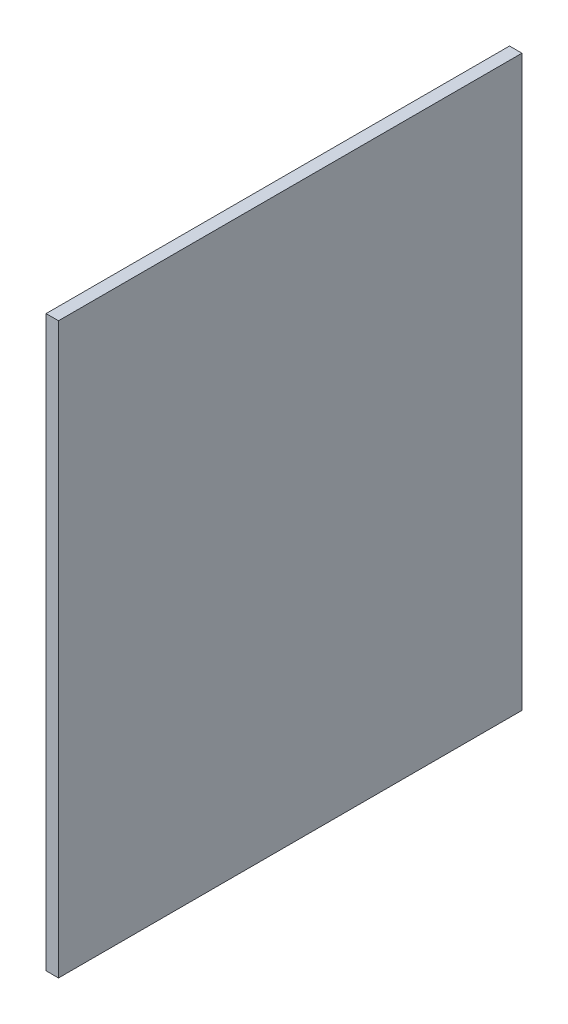
SolidWorks part; units mm, degrees
material "Acrylic (Medium-high impact)"
ref_plane "Front Plane" through (0, 0, 0) normal (0, 0, 1) x (1, 0, 0)
ref_plane "Top Plane" through (0, 0, 0) normal (0, 1, 0) x (1, 0, 0)
ref_plane "Right Plane" through (0, 0, 0) normal (1, 0, 0) x (0, 0, -1)
sketch "Sketch2" plane through (0, 0, 0) normal (1, 0, 0) x (0, 0, -1)
  line L1 (-409.575, 517.525) -> (409.575, 517.525)
  line L2 (-409.575, 517.525) -> (-409.575, -517.525)
  line L3 (-409.575, -517.525) -> (409.575, -517.525)
  line L4 (409.575, 517.525) -> (409.575, -517.525)
  line L5 (-409.575, 517.525) -> (409.575, -517.525) construction
  line L6 (-409.575, -517.525) -> (409.575, 517.525) construction
  point P0 (0, 0)
extrude "Boss-Extrude1" add sketch "Sketch2" along normal blind 25.4
sketch "Sketch3" plane through (25.4, 0, 0) normal (1, 0, 0) x (0, 0, -1)
  line L1 (447.675, -555.625) -> (-447.675, -555.625)
  line L2 (447.675, -555.625) -> (447.675, 555.625)
  line L3 (447.675, 555.625) -> (-447.675, 555.625)
  line L4 (409.575, -517.525) -> (409.575, 517.525)
  line L5 (409.575, 517.525) -> (-409.575, 517.525)
  line L6 (-409.575, 517.525) -> (-409.575, -517.525)
  line L7 (-409.575, -517.525) -> (409.575, -517.525)
  line L8 (409.575, -517.525) -> (409.575, 517.525)
  line L9 (409.575, 517.525) -> (-409.575, 517.525)
  line L10 (-409.575, 517.525) -> (-409.575, -517.525)
  line L11 (-409.575, -517.525) -> (409.575, -517.525)
  line L12 (-447.675, -555.625) -> (-447.675, 555.625)
  line L13 (447.675, -555.625) -> (-447.675, 555.625) construction
  line L14 (447.675, 555.625) -> (-447.675, -555.625) construction
  point P2 (0, 0)
  dimension "D1" = 0
extrude "Boss-Extrude2" add sketch "Sketch3" against normal blind 25.4
sketch "Sketch4" plane through (25.4, 0, 0) normal (1, 0, 0) x (0, 0, -1)
  line L1 (-473.075, 581.025) -> (473.075, 581.025)
  line L2 (-473.075, 581.025) -> (-473.075, -581.025)
  line L3 (-473.075, -581.025) -> (473.075, -581.025)
  line L4 (473.075, 581.025) -> (473.075, -581.025)
  line L5 (-473.075, 581.025) -> (473.075, -581.025) construction
  line L6 (-473.075, -581.025) -> (473.075, 581.025) construction
  point P1 (0, 0)
extrude "Boss-Extrude3" add sketch "Sketch4" against normal blind 25.4
